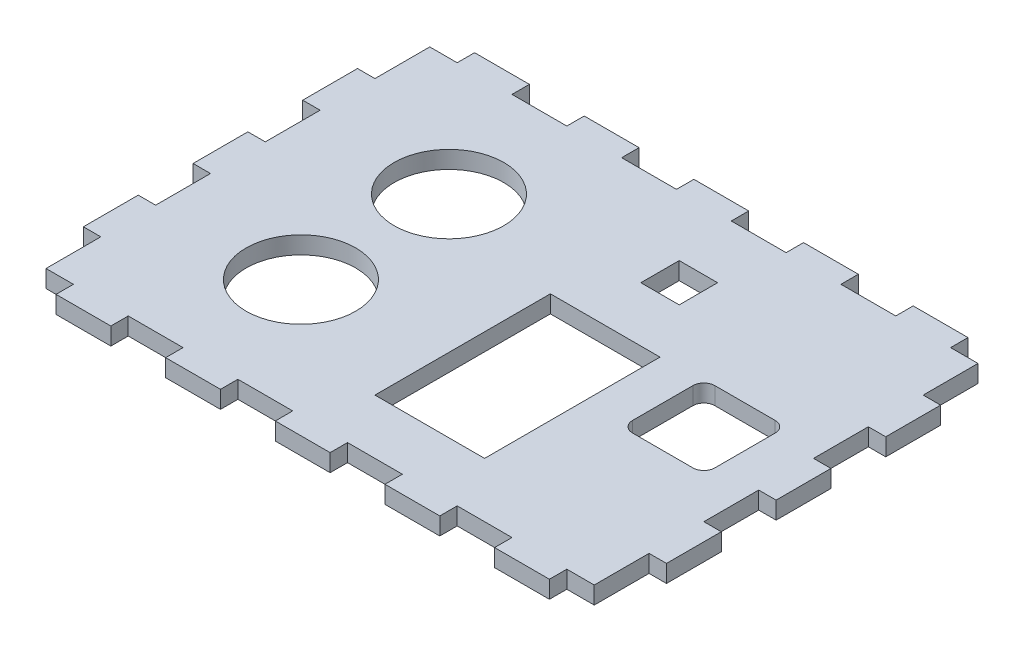
SolidWorks part; units mm, degrees
material "Acrylic (Medium-high impact)"
ref_plane "Front Plane" through (0, 0, 0) normal (0, 0, 1) x (1, 0, 0)
ref_plane "Top Plane" through (0, 0, 0) normal (0, 1, 0) x (1, 0, 0)
ref_plane "Right Plane" through (0, 0, 0) normal (1, 0, 0) x (0, 0, -1)
sketch "Sketch1" plane through (0, 0, 0) normal (0, 1, 0) x (1, 0, 0)
  line L1 (0, 0) -> (100, 0)
  line L2 (0, 0) -> (0, 70)
  line L3 (0, 70) -> (100, 70)
  line L4 (100, 0) -> (100, 70)
  dimension "D1" = 100
  dimension "D2" = 70
extrude "Boss-Extrude1" add sketch "Sketch1" along normal blind 3.175
sketch "Sketch3" plane through (0, 0, 0) normal (0, 1, 0) x (1, 0, 0)
  line L0 (100, 70) -> (0, 70) construction
  line L1 (5, 70) -> (15, 70)
  line L2 (5, 70) -> (5, 73.175)
  line L3 (5, 73.175) -> (15, 73.175)
  line L4 (15, 70) -> (15, 73.175)
  line L5 (-3.175, 10) -> (0, 10)
  line L6 (-3.175, 30) -> (0, 30)
  line L7 (-3.175, 30) -> (-3.175, 40)
  line L8 (-3.175, 40) -> (0, 40)
  line L9 (0, 30) -> (0, 40)
  line L10 (0, 70) -> (0, 0) construction
  line L11 (-11.3065, 35) -> (117.1346, 35) construction
  line L36 (5, 70) -> (20, 70) construction
  line L53 (50, -4.7166) -> (50, 86.7959) construction
  line L54 (25, 70) -> (25, 73.175)
  line L55 (25, 70) -> (35, 70)
  line L56 (35, 70) -> (35, 73.175)
  line L57 (25, 73.175) -> (35, 73.175)
  line L58 (45, 70) -> (45, 73.175)
  line L59 (45, 70) -> (55, 70)
  line L60 (55, 70) -> (55, 73.175)
  line L61 (45, 73.175) -> (55, 73.175)
  line L62 (65, 70) -> (65, 73.175)
  line L63 (65, 70) -> (75, 70)
  line L64 (75, 70) -> (75, 73.175)
  line L65 (65, 73.175) -> (75, 73.175)
  line L66 (85, 70) -> (85, 73.175)
  line L67 (85, 70) -> (95, 70)
  line L68 (95, 70) -> (95, 73.175)
  line L69 (85, 73.175) -> (95, 73.175)
  line L70 (5, 70) -> (25, 70) construction
  line L71 (0, 0) -> (100, 0) construction
  line L72 (0, 10) -> (0, 20)
  line L73 (-3.175, 20) -> (0, 20)
  line L74 (-3.175, 10) -> (-3.175, 20)
  line L75 (-3.175, 30) -> (0, 30)
  line L76 (0, 30) -> (0, 40)
  line L77 (-3.175, 40) -> (0, 40)
  line L78 (-3.175, 30) -> (-3.175, 40)
  line L83 (-3.175, 30) -> (-3.175, 10) construction
  line L84 (-3.175, 50) -> (0, 50) [skipped]
  line L85 (0, 50) -> (0, 60) [skipped]
  line L86 (-3.175, 60) -> (0, 60) [skipped]
  line L87 (-3.175, 50) -> (-3.175, 60) [skipped]
  line L88 (-3.175, 50) -> (0, 50)
  line L89 (0, 50) -> (0, 60)
  line L90 (-3.175, 60) -> (0, 60)
  line L91 (-3.175, 50) -> (-3.175, 60)
  line L92 (-3.175, 30) -> (-3.175, 50) construction
  point P11 (-3.175, 35)
  point P17 (0, 35)
  point P40 (50, 0)
  dimension "D1" = 10
  dimension "D2" = 3.175
  dimension "D3" = 5
  dimension "D4" = 2
  dimension "D5" = 3.175
  dimension "D6" = 10
  dimension "D8" = 15
  dimension "D10" = 20
  dimension "D11" = 20
  dimension "D13" = 20
  dimension "D7" = 5
  dimension "D9" = 2
  dimension "D12" = 2
extrude "Boss-Extrude2" add sketch "Sketch3" along normal blind 3.175 contours L91 L88 L89 L90 | L6 L9 L8 L7 | L74 L5 L72 L73 | L57 L54 L55 L56 | L65 L62 L63 L64 | L69 L66 L67 L68 | L3 L4 L1 L2 | L59 L60 L61 L58
ref_plane "Plane1" through (0, 0, -35) normal (0, 0, -1) x (-1, 0, 0)
ref_plane "Plane2" through (50, 0, 0) normal (1, 0, 0) x (0, 0, -1)
mirror "Mirror1" about plane through (50, 0, 0) normal (1, 0, 0) of "Boss-Extrude2"
mirror "Mirror2" about plane through (0, 0, -35) normal (0, 0, -1) of "Mirror1"
sketch "Sketch4" plane through (0, 0, 0) normal (0, -1, 0) x (1, 0, 0)
  line L0 (100, -20) -> (100, -30) construction
  line L1 (50, -10) -> (70, -10)
  line L2 (50, -10) -> (50, -42)
  line L3 (50, -42) -> (70, -42)
  line L4 (70, -10) -> (70, -42)
  line L5 (56.5, -52) -> (63.5, -52)
  line L6 (56.5, -52) -> (56.5, -59)
  line L7 (56.5, -59) -> (63.5, -59)
  line L8 (63.5, -52) -> (63.5, -59)
  line L9 (77.5, -27.5) -> (92.5, -27.5)
  line L10 (77.5, -27.5) -> (77.5, -42.5)
  line L11 (77.5, -42.5) -> (92.5, -42.5)
  line L12 (92.5, -27.5) -> (92.5, -42.5)
  line L13 (100, 0) -> (100, -10) construction
  line L14 (75, 0) -> (85, 0) construction
  line L17 (-11.3065, -35) -> (117.1346, -35) construction
  point P15 (60, -52)
  point P16 (60, -42)
  point P35 (77.5, -35)
  dimension "D1" = 32
  dimension "D2" = 20
  dimension "D3" = 7
  dimension "D4" = 10
  dimension "D5" = 30
  dimension "D6" = 10
  dimension "D7" = 15
  dimension "D8" = 7.5
extrude "Cut-Extrude1" cut sketch "Sketch4" against normal through all both and the other way through all
fillet "Fillet1" radius 2 4 edges at (92.5, 1.5875, -42.5) (77.5, 1.5875, -42.5) (77.5, 1.5875, -27.5) (92.5, 1.5875, -27.5)
sketch "Sketch5" plane through (0, 0, 0) normal (0, -1, 0) x (1, 0, 0)
  line L2 (5, -70) -> (25, -70) construction
  line L3 (0, -70) -> (0, -60) construction
  line L4 (-11.3065, -35) -> (117.1346, -35) construction
  circle A0 centre (25, -48.5) radius 10
  circle A1 centre (25, -21.5) radius 10
  dimension "D1" = 20
  dimension "D2" = 21.5
  dimension "D3" = 25
extrude "Cut-Extrude2" cut sketch "Sketch5" against normal through all both and the other way through all
